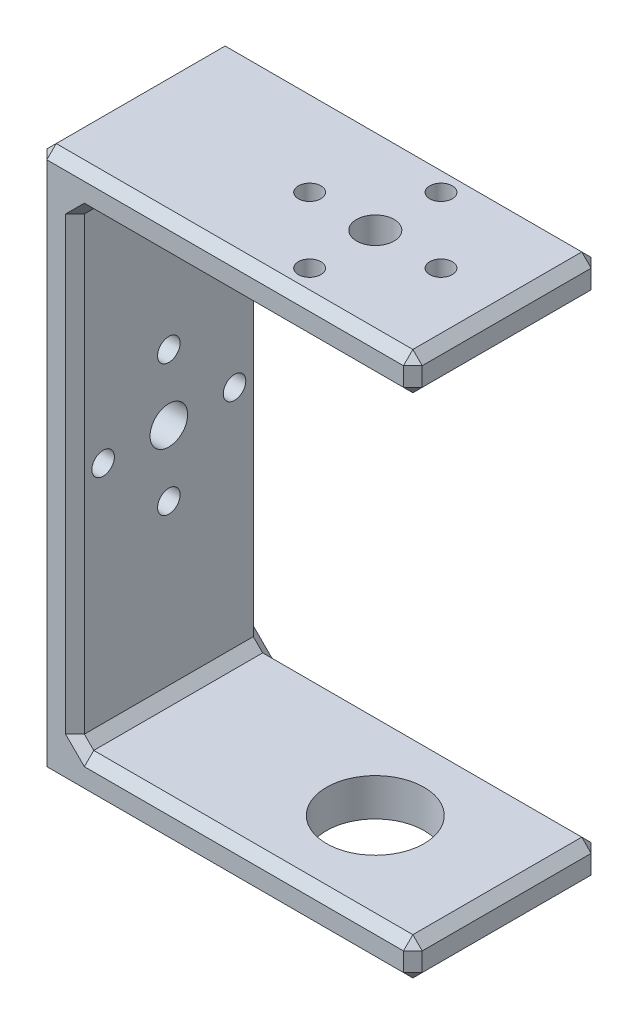
SolidWorks part; units mm, degrees
material "ABS"
ref_plane "Front Plane" through (0, 0, 0) normal (0, 0, 1) x (1, 0, 0)
ref_plane "Top Plane" through (0, 0, 0) normal (0, 1, 0) x (1, 0, 0)
ref_plane "Right Plane" through (0, 0, 0) normal (1, 0, 0) x (0, 0, -1)
sketch "Sketch1" plane through (0, 0, 0) normal (1, 0, 0) x (0, 0, -1)
  line L1 (-10, 25) -> (10, 25)
  line L2 (-10, 25) -> (-10, -25)
  line L3 (-10, -25) -> (10, -25)
  line L4 (10, 25) -> (10, -25)
  line L5 (-10, 25) -> (10, -25) construction
  line L6 (-10, -25) -> (10, 25) construction
  point P0 (0, 0)
  dimension "D1" = 50
  dimension "D2" = 20
extrude "Boss-Extrude1" add sketch "Sketch1" along normal blind 4
sketch "Sketch2" plane through (0, 25, 0) normal (0, 1, 0) x (1, 0, 0)
  line L0 (4, 10) -> (0, 10) construction
  line L1 (0, -10) -> (40, -10)
  line L2 (0, -10) -> (0, 10)
  line L3 (0, 10) -> (40, 10)
  line L4 (40, -10) -> (40, 10)
  dimension "D1" = 40
extrude "Boss-Extrude2" add sketch "Sketch2" along normal blind 4
sketch "Sketch3" plane through (0, 29, 0) normal (0, 1, 0) x (1, 0, 0)
  circle A0 centre (26, 0) radius 2
  circle A1 centre (19, 0) radius 1.2
  circle A2 centre (26, 0) radius 2
  circle A3 centre (26, 7) radius 1.2
  circle A4 centre (26, 0) radius 2
  circle A5 centre (33, 0) radius 1.2
  circle A6 centre (26, 0) radius 2
  circle A7 centre (26, -7) radius 1.2
  point P17 (26, 0)
  dimension "D1" = 4
  dimension "D4" = 2.4
  dimension "D2" = 7
  dimension "D3" = 26
  dimension "D5" = 4
extrude "Cut-Extrude1" cut sketch "Sketch3" against normal blind 4 contours A5 | A0 | A7 | A1 | A3
sketch "Sketch4" plane through (0, -25, 0) normal (0, -1, 0) x (1, 0, 0)
  line L1 (0, -10) -> (40, -10)
  line L2 (0, -10) -> (0, 10)
  line L3 (0, 10) -> (40, 10)
  line L4 (40, -10) -> (40, 10)
extrude "Boss-Extrude3" add sketch "Sketch4" along normal blind 4
sketch "Sketch5" plane through (0, -29, 0) normal (0, -1, 0) x (1, 0, 0)
  circle A0 centre (26, 0) radius 5.2
  dimension "D1" = 10.4
  dimension "D2" = 26
extrude "Cut-Extrude2" cut sketch "Sketch5" against normal blind 4
chamfer "Chamfer1" distance 1 angle 45 24 edges at (22, -25, -10) (40, -27, 10) (40, -27, -10) (40, -29, 0) (40, -25, 0) (22, -25, 10) (4, -25, 0) (40, 27, -10) (40, 25, 0) (4, 0, -10) (22, 25, -10) (4, 25, 0) (4, 0, 10) (22, 25, 10) (40, 27, 10) (20, -29, 10) (20, -29, -10) (40, 29, 0) (20, 29, -10) (20, 29, 10) (0, 0, -10) (0, -29, 0) (0, 0, 10) (0, 29, 0)
sketch "Sketch6" plane through (0, 0, 0) normal (-1, 0, 0) x (0, 0, 1)
  circle A0 centre (0, 0) radius 2
  circle A1 centre (7, 0) radius 1.2
  circle A4 centre (0, -7) radius 1.2
  circle A5 centre (-7, 0) radius 1.2
  circle A6 centre (0, 7) radius 1.2
  point P14 (0, 0)
  dimension "D1" = 4
  dimension "D2" = 2.4
  dimension "D3" = 7
  dimension "D4" = 4
extrude "Cut-Extrude3" cut sketch "Sketch6" against normal blind 10
